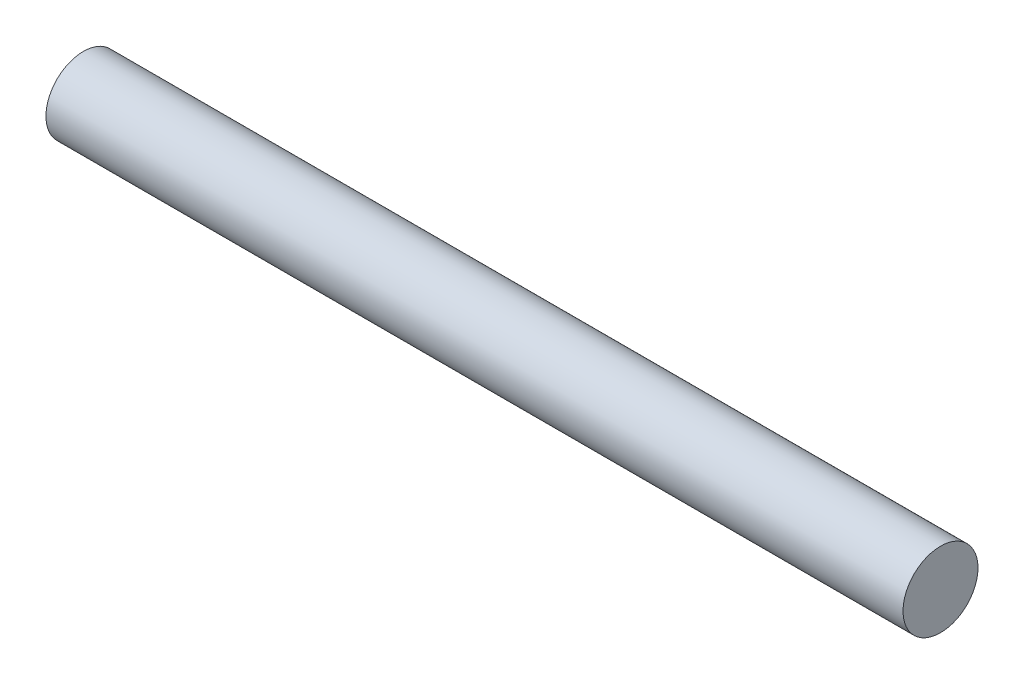
SolidWorks part; units mm, degrees
material "Brass"
ref_plane "Front Plane" through (0, 0, 0) normal (0, 0, 1) x (1, 0, 0)
ref_plane "Top Plane" through (0, 0, 0) normal (0, 1, 0) x (1, 0, 0)
ref_plane "Right Plane" through (0, 0, 0) normal (1, 0, 0) x (0, 0, -1)
sketch "Sketch1" plane through (0, 0, 0) normal (1, 0, 0) x (0, 0, -1)
  circle A0 centre (0, 0) radius 2.5
  dimension "D1" = 5
extrude "Base" add sketch "Sketch1" along normal blind 57.15
